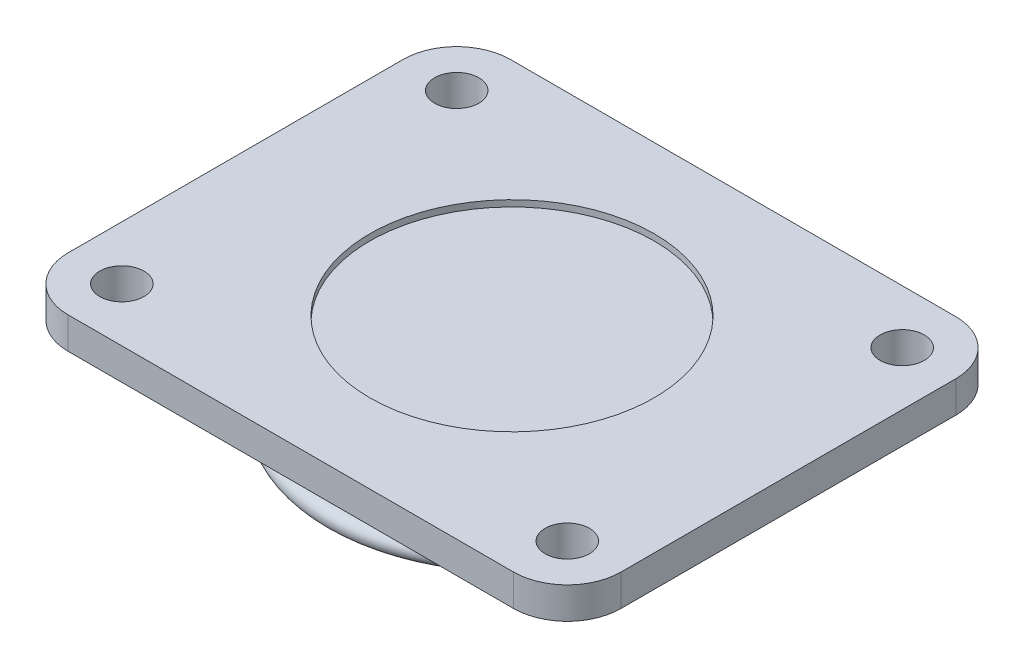
SolidWorks part; units mm, degrees
ref_plane "Front Plane" through (0, 0, 0) normal (0, 0, 1) x (1, 0, 0)
ref_plane "Top Plane" through (0, 0, 0) normal (0, 1, 0) x (1, 0, 0)
ref_plane "Right Plane" through (0, 0, 0) normal (1, 0, 0) x (0, 0, -1)
sketch "Sketch1" plane through (0, 0, 0) normal (0, 1, 0) x (1, 0, 0)
  line L1 (70.5, -70) -> (-70.5, -70)
  line L2 (87.5, -53) -> (87.5, 53)
  line L3 (70.5, 70) -> (-70.5, 70)
  line L4 (-87.5, -53) -> (-87.5, 53)
  line L5 (87.5, -70) -> (-87.5, 70) construction
  line L6 (87.5, 70) -> (-87.5, -70) construction
  arc A0 (-70.5, -70) -> (-87.5, -53) centre (-70.5, -53) cw
  arc A1 (70.5, -70) -> (87.5, -53) centre (70.5, -53) ccw
  arc A2 (87.5, 53) -> (70.5, 70) centre (70.5, 53) ccw
  arc A3 (-70.5, 70) -> (-87.5, 53) centre (-70.5, 53) ccw
  circle A4 centre (-70.5, 53) radius 7
  circle A5 centre (70.5, 53) radius 7
  circle A6 centre (70.5, -53) radius 7
  circle A7 centre (-70.5, -53) radius 7
  point P0 (0, 0)
  dimension "D3" = 17
  dimension "D4" = 14
  dimension "D1" = 175
  dimension "D2" = 140
extrude "Boss-Extrude1" add sketch "Sketch1" along normal blind 10
sketch "Sketch3" plane through (0, 0, 0) normal (0, -1, 0) x (1, 0, 0)
  circle A0 centre (0, 0) radius 56
  dimension "D1" = 112
extrude "Boss-Extrude2" add sketch "Sketch3" along normal blind 20
sketch "Sketch4" plane through (0, 0, 0) normal (1, 0, 0) x (0, 0, -1)
  line L7 (-56, 0) -> (-56, -20) construction
  line L8 (0, 0) -> (0, -28.733) construction
  line L9 (-56, -20) -> (56, -20) construction
  circle A8 centre (-56, -17) radius 3
  dimension "D1" = 6
revolve "Revolve1" add sketch "Sketch4" angle 360 about L8
sketch "Sketch5" plane through (0, -20, 0) normal (0, -1, 0) x (1, 0, 0)
  circle A0 centre (0, 0) radius 7.5
  dimension "D1" = 15
extrude "Boss-Extrude3" add sketch "Sketch5" along normal blind 25
cosmetic thread "Cosmetic Thread1" parameters "D2"=11.797
chamfer "Chamfer1" distance 1 angle 45 1 edges at (0, -45, -7.5)
sketch "Sketch6" plane through (0, 10, 0) normal (0, 1, 0) x (1, 0, 0)
  circle A0 centre (0, 0) radius 45
  dimension "D1" = 90
extrude "Cut-Extrude1" cut sketch "Sketch6" against normal blind 2
